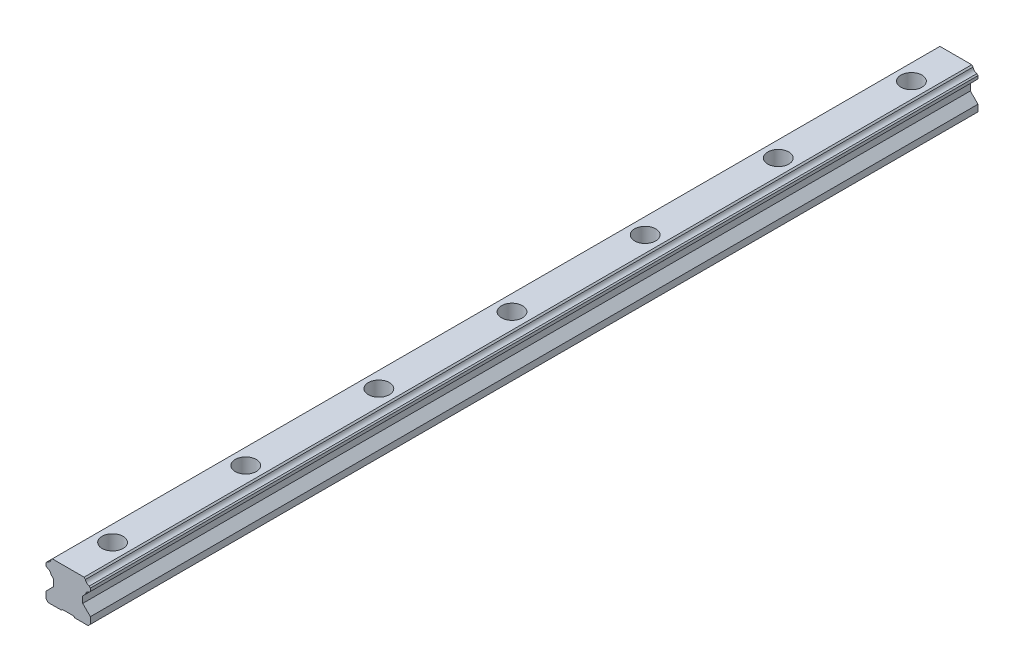
SolidWorks part; units mm, degrees
material "Plain Carbon Steel"
ref_plane "Front Plane" through (0, 0, 0) normal (0, 0, 1) x (1, 0, 0)
ref_plane "Top Plane" through (0, 0, 0) normal (0, 1, 0) x (1, 0, 0)
ref_plane "Right Plane" through (0, 0, 0) normal (1, 0, 0) x (0, 0, -1)
sketch "Sketch1" plane through (0, 0, 0) normal (0, 0, 1) x (1, 0, 0)
  line L0 (-10, -10.4945) -> (-10, -13.4946)
  line L1 (-10, -13.4946) -> (-9, -14.4946)
  line L2 (-9, -14.4946) -> (-3, -14.4946)
  line L3 (-3, -14.4946) -> (-2.5, -13.9946)
  line L4 (-2.5, -13.9946) -> (2.5, -13.9946)
  line L5 (6.55, -7.0447) -> (10, -10.4945)
  line L6 (6.55, -4.1154) -> (6.55, -7.0447)
  line L7 (7.7679, -2.8995) -> (6.55, -4.1154)
  line L8 (10, -0.6654) -> (9.4727, -1.1802)
  line L9 (10, 0.6654) -> (10, -0.6654)
  line L10 (9.4727, 1.1928) -> (10, 0.6654)
  line L11 (7.16, 3.5054) -> (7.7679, 2.8975)
  line L12 (3, -14.4946) -> (2.5, -13.9946)
  line L13 (9, -14.4946) -> (3, -14.4946)
  line L14 (10, -13.4946) -> (9, -14.4946)
  line L15 (10, -10.4945) -> (10, -13.4946)
  line L16 (7.16, 3.5054) -> (-7.16, 3.5054)
  line L17 (-7.16, 3.5054) -> (-7.7679, 2.8975)
  line L18 (-9.4727, 1.1928) -> (-10, 0.6654)
  line L19 (-10, 0.6654) -> (-10, -0.6654)
  line L20 (-10, -0.6654) -> (-9.4727, -1.1802)
  line L21 (-7.7679, -2.8995) -> (-6.55, -4.1154)
  line L22 (-6.55, -4.1154) -> (-6.55, -7.0447)
  line L23 (-6.55, -7.0447) -> (-10, -10.4945)
  line L24 (0, -14.4946) -> (0, -13.9946) construction
  line L25 (0, -13.9946) -> (0, 3.5054) construction
  line L26 (55, 0) -> (-55, 0) construction
  arc A0 (9.4727, -1.1802) -> (7.7679, -2.8995) centre (9.8039, -3.2134) ccw
  arc A1 (7.7679, 2.8975) -> (9.4727, 1.1928) centre (9.8015, 3.2263) ccw
  arc A2 (-7.7679, 2.8975) -> (-9.4727, 1.1928) centre (-9.8015, 3.2263) cw
  arc A3 (-9.4727, -1.1802) -> (-7.7679, -2.8995) centre (-9.8039, -3.2134) cw
  point P38 (10, 0)
  dimension "D17" = 2.06
  dimension "D1" = 20
  dimension "D2" = 1
  dimension "D3" = 1
  dimension "D4" = 0.5
  dimension "D5" = 0.5
  dimension "D6" = 6
  dimension "D7" = 18
  dimension "D8" = 4.0001
  dimension "D9" = 10.55
  dimension "D10" = 13.1001
  dimension "D11" = 15.5359
  dimension "D12" = 0.6079
  dimension "D13" = 0.6079
  dimension "D14" = 17.5
  dimension "D15" = 0.5273
  dimension "D16" = 0.5273
  dimension "D18" = 1.2159
  dimension "D19" = 0.5148
  dimension "D20" = 6.4049
  dimension "D21" = 2.84
  dimension "D22" = 4.1708
extrude "Boss-Extrude1" add sketch "Sketch1" against normal mid plane 400
sketch "Sketch2" plane through (0, 0, 0) normal (1, 0, 0) x (0, 0, -1)
  line L0 (-180, 3.5054) -> (-180, -14.4946)
  line L1 (200, 3.5054) -> (-200, 3.5054) construction
  line L2 (200, -14.4946) -> (-200, -14.4946) construction
  line L3 (-180, -14.4946) -> (-183, -14.4946)
  line L4 (-183, -14.4946) -> (-183, -4.9946)
  line L5 (-183, -4.9946) -> (-184.75, -4.9946)
  line L6 (-184.75, -4.9946) -> (-184.75, 3.5054)
  line L7 (-184.75, 3.5054) -> (-180, 3.5054)
  line L8 (-200, -7.0447) -> (-200, -4.1154) construction
  point P12 (-200, -5.58)
  dimension "D1" = 3
  dimension "D2" = 4.75
  dimension "D3" = 8.5
  dimension "D4" = 20
revolve "Cut-Revolve1" cut sketch "Sketch2" angle 360 about L0
pattern_linear "LPattern1" count 7 spacing 60 along (0, 0, -1) of "Cut-Revolve1"
equation "\"Length\"= 400"
equation "\"Pitch\"= 60mm"
equation "\"Holes\"= int ( ( \"Length\" + \"Pitch\" / 2 ) / \"Pitch\" )"
equation "\"EndSpacing\"= ( \"Length\" - \"Pitch\" * ( \"Holes\" - 1 ) ) / 2"
equation "\"D4@Sketch2\"=\"EndSpacing\""
equation "\"D3@LPattern1\"=\"Pitch\""
equation "\"D1@LPattern1\"=\"Holes\""
equation "\"D1@Boss-Extrude1\"=\"Length\""
